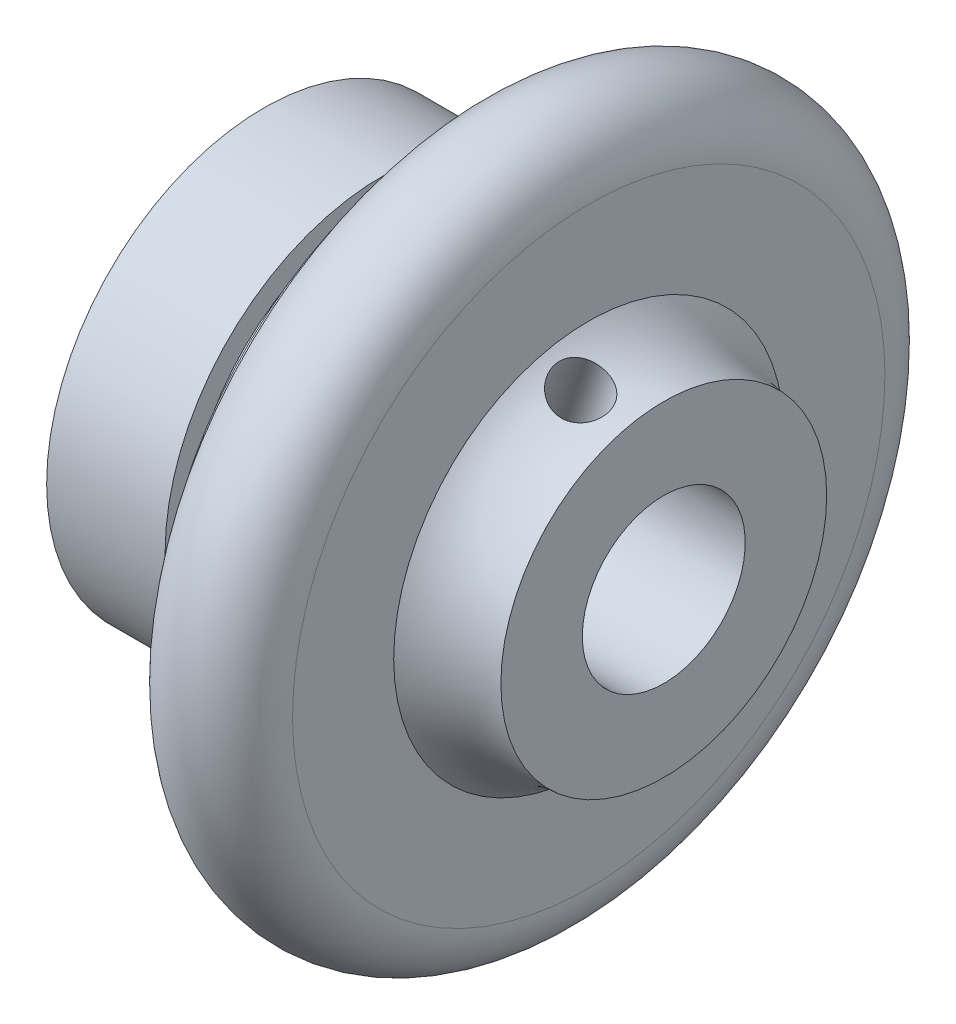
SolidWorks part; units mm, degrees
ref_plane "Front Plane" through (0, 0, 0) normal (0, 0, 1) x (1, 0, 0)
ref_plane "Top Plane" through (0, 0, 0) normal (0, 1, 0) x (1, 0, 0)
ref_plane "Right Plane" through (0, 0, 0) normal (1, 0, 0) x (0, 0, -1)
sketch "Sketch2" plane through (0, 0, 0) normal (0, 0, 1) x (1, 0, 0)
  line L0 (0, 5.5) -> (27, 5.5)
  line L1 (27, 5.5) -> (27, 11)
  line L2 (21.9333, 13.17) -> (21.9333, 20)
  line L3 (13.9333, 20) -> (12.9333, 20)
  line L4 (12.9333, 20) -> (12.9333, 13.17)
  line L5 (12.9333, 13.17) -> (8, 13.17)
  line L6 (8, 13.17) -> (8, 14.67)
  line L7 (8, 14.67) -> (0, 14.67)
  line L8 (0, 14.67) -> (0, 5.5)
  line L9 (0, 0) -> (49.3483, 0) construction
  arc A0 (27, 11) -> (21.9333, 13.17) centre (27, 18) cw
  arc A2 (13.9333, 20) -> (21.9333, 20) centre (17.9333, 20) cw
  dimension "D4" = 7
  dimension "D6" = 14.67
  dimension "D5" = 4
  dimension "D1" = 27
  dimension "D2" = 5.5
  dimension "D3" = 11
  dimension "D7" = 1
  dimension "D8" = 8
  dimension "D9" = 20
  dimension "D10" = 20
  dimension "D11" = 1.5
revolve "Revolve1" add sketch "Sketch2" angle 360 about L9
cosmetic thread "Cosmetic Thread1" parameters "D1"=8, "D2"=24.2545
hole_wizard "Ø3.5 (3.5) Diameter Hole1" positions "3DSketch1" profile "Sketch3" hole size "Ø3.5" standard "ANSI Metric"
sketch3d "3DSketch1"
  point P0 (23.9702, 11.3988, 2.5912)
sketch "Sketch3" plane through (23.9702, 11.3988, 2.5912) normal (0.6302, -0.4536, 0.6302) x (-0.6446, 0.1468, 0.7503)
  line L0 (0, 0) -> (0, 13.75)
  line L1 (0, 13.75) -> (1.75, 12)
  line L2 (1.75, 12) -> (1.75, 0)
  line L5 (1.75, 0) -> (0, 0)
  line L10 (0, 13.75) -> (-1.75, 12) construction
  line L11 (0, -6.35) -> (0, 107.95) construction
  dimension "Hole Dia." = 3.5
  dimension "Hole Depth" = 12
  dimension "Drill Angle" = 90
